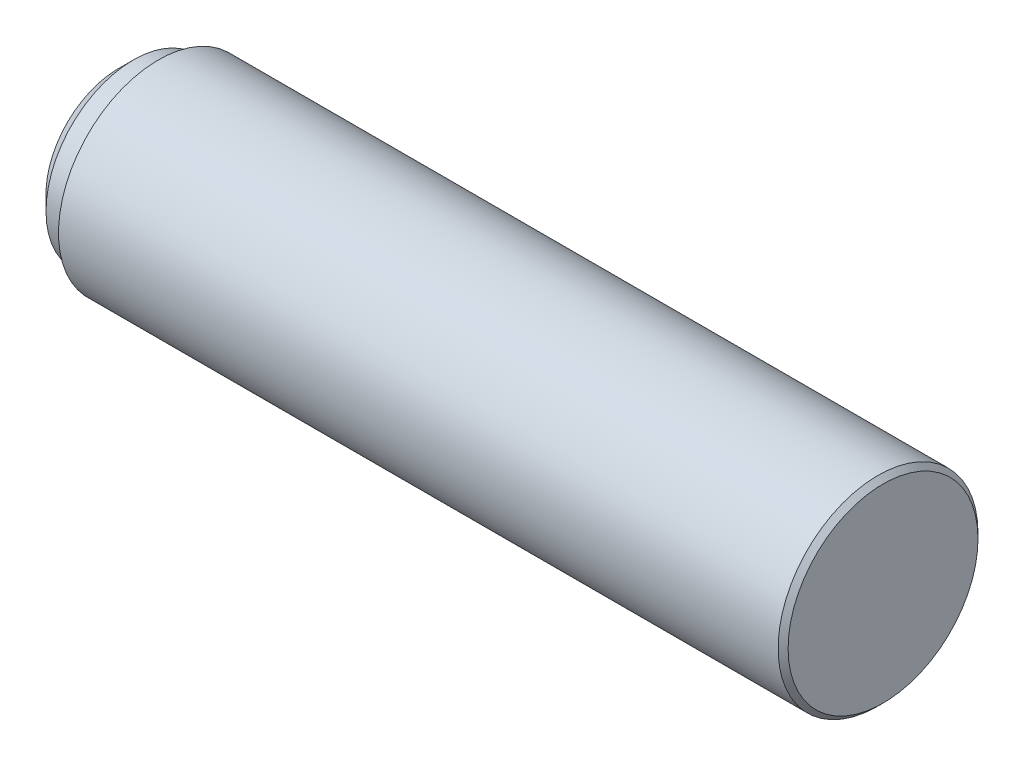
SolidWorks part; units mm, degrees
material "45"
ref_plane "前视基准面" through (0, 0, 0) normal (0, 0, 1) x (1, 0, 0)
ref_plane "上视基准面" through (0, 0, 0) normal (0, 1, 0) x (1, 0, 0)
ref_plane "右视基准面" through (0, 0, 0) normal (1, 0, 0) x (0, 0, -1)
sketch "草图1" plane through (0, 0, 0) normal (1, 0, 0) x (0, 0, -1)
  circle A0 centre (0, 0) radius 20
  dimension "D1" = 40
extrude "凸台-拉伸1" add sketch "草图1" along normal blind 145
sketch "草图2" plane through (0, 0, 0) normal (-1, 0, 0) x (0, 0, 1)
  circle A0 centre (0, 0) radius 17.5
  dimension "D1" = 35
extrude "凸台-拉伸2" add sketch "草图2" along normal blind 8
chamfer "倒角2" distance 3 angle 45 1 edges at (-8, 0, 17.5)
chamfer "倒角1" distance 1 angle 45 1 edges at (145, 0, -20)
